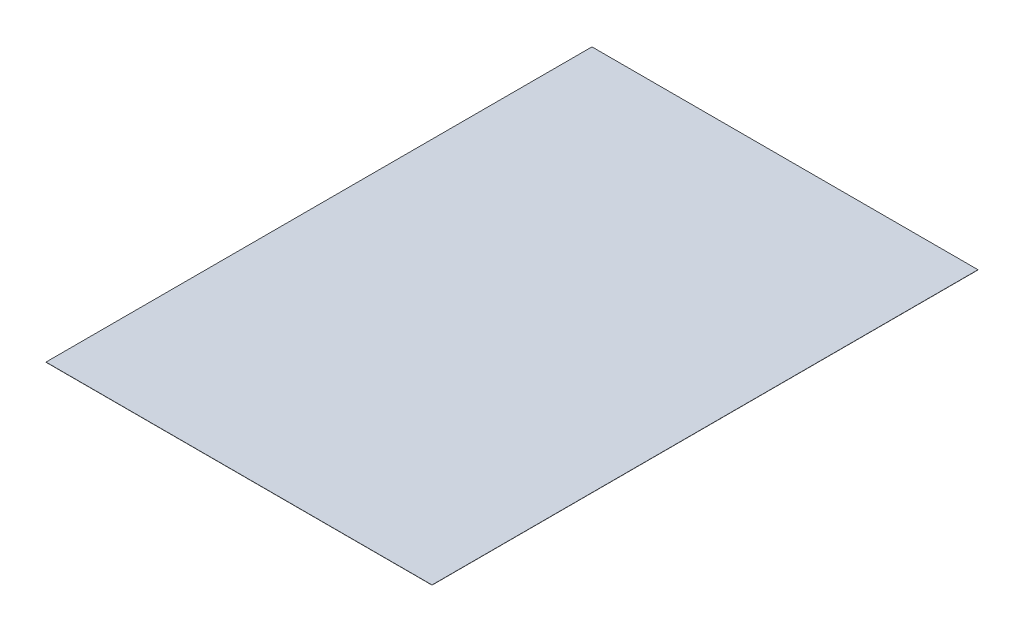
SolidWorks part; units mm, degrees
ref_plane "Front Plane" through (0, 0, 0) normal (0, 0, 1) x (1, 0, 0)
ref_plane "Top Plane" through (0, 0, 0) normal (0, 1, 0) x (1, 0, 0)
ref_plane "Right Plane" through (0, 0, 0) normal (1, 0, 0) x (0, 0, -1)
sketch "Sketch1" plane through (0, 0, 0) normal (0, 1, 0) x (1, 0, 0)
  line L0 (63.638, 56.1771) -> (310.9713, 56.1771) construction
  line L1 (0, 0) -> (210, 0)
  line L2 (0, 0) -> (0, 297)
  line L3 (0, 297) -> (210, 297)
  line L4 (210, 0) -> (210, 297)
  dimension "D1" = 210
  dimension "D2" = 297
extrude "Boss-Extrude1" add sketch "Sketch1" along normal blind 0.1
